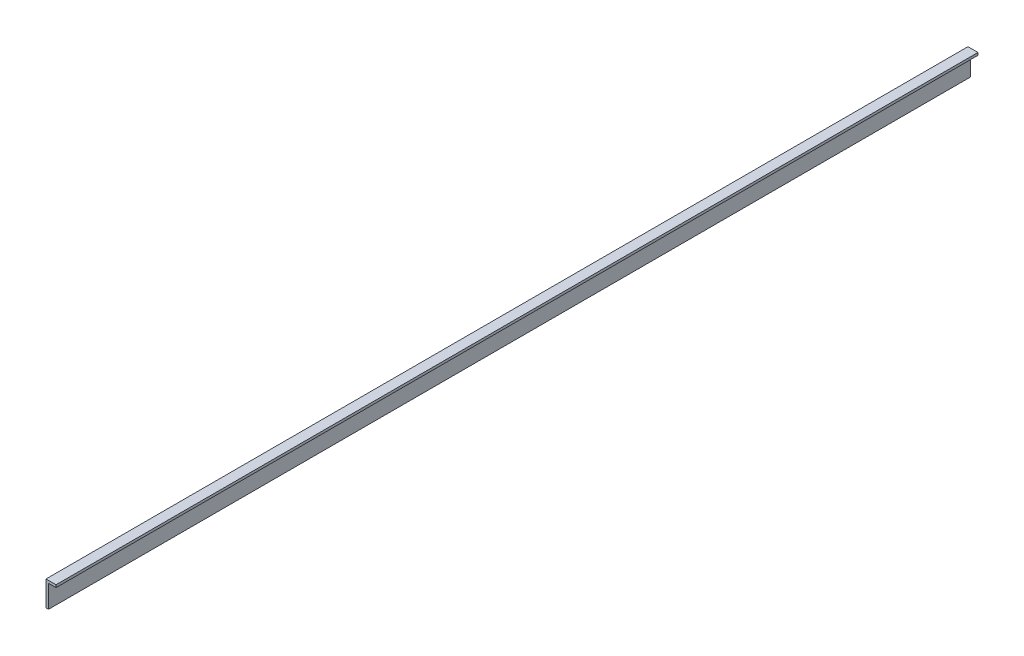
SolidWorks part; units mm, degrees
ref_plane "Front Plane" through (0, 0, 0) normal (0, 0, 1) x (1, 0, 0)
ref_plane "Top Plane" through (0, 0, 0) normal (0, 1, 0) x (1, 0, 0)
ref_plane "Right Plane" through (0, 0, 0) normal (1, 0, 0) x (0, 0, -1)
other "Configuration Table"
sketch "Sketch1" plane through (0, 0, 0) normal (0, 0, 1) x (1, 0, 0)
  line L0 (393.5, 404.5) -> (391.5, 404.5)
  line L1 (391.5, 404.5) -> (391.5, 424.5)
  line L2 (391.5, 424.5) -> (399.5, 424.5)
  line L3 (399.5, 424.5) -> (399.5, 422.5)
  line L4 (399.5, 422.5) -> (393.5, 422.5)
  line L5 (393.5, 422.5) -> (393.5, 404.5)
extrude "STORE_kaset_L_raf_3_sol_1" add sketch "Sketch1" against normal blind 735.5 from offset 20 separate body
